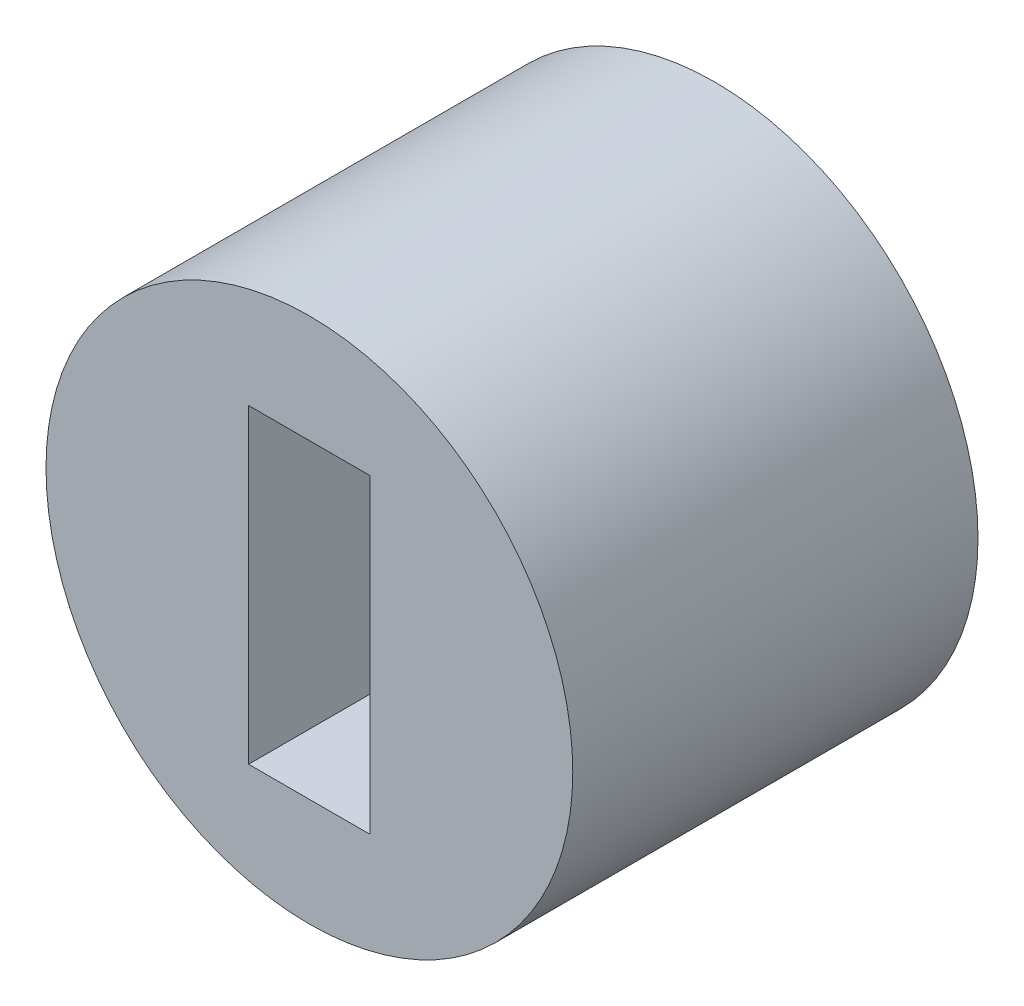
SolidWorks part; units mm, degrees
ref_plane "Front" through (0, 0, 0) normal (0, 0, 1) x (1, 0, 0)
ref_plane "Top" through (0, 0, 0) normal (0, 1, 0) x (1, 0, 0)
ref_plane "Right" through (0, 0, 0) normal (1, 0, 0) x (0, 0, -1)
sketch "Sketch1" plane through (0, 0, 0) normal (0, 0, 1) x (1, 0, 0)
  line L1 (0, -3.9574) -> (0, 4.0973) construction
  line L2 (-0.45, -1.15) -> (-0.45, 1.15)
  line L3 (-0.45, 1.15) -> (0.45, 1.15)
  line L4 (0.45, 1.15) -> (0.45, -1.15)
  line L5 (0.45, -1.15) -> (-0.45, -1.15)
  line L6 (0.45, -1.15) -> (-0.45, 1.15) construction
  line L7 (0.45, 1.15) -> (-0.45, -1.15) construction
  circle A0 centre (0, 0) radius 1.95
  point P1 (0, 0)
  dimension "D1" = 3.9
  dimension "D2" = 2.3
  dimension "D3" = 0.9
extrude "ext-body" add sketch "Sketch1" against normal blind 3
equation "\"rad-pot\"= 3.9mm"
equation "\"len-dimlen\"= 3.8"
equation "\"len-flatbar\"= ( \"rad-pot\" / 2 ) - ( \"rad-pot\" - \"len-dimlen\" )"
equation "\"D1@Sketch1\"=\"rad-pot\""
equation "\"ang-flatbar\"= 20deg"
equation "\"th-pot\"= 3mm"
equation "\"D1@ext-body\" = \"th-pot\""
equation "\"th-pot_body\"= 3.9mm"
equation "\"D2@ext-body\" = \"th-pot_body\""
